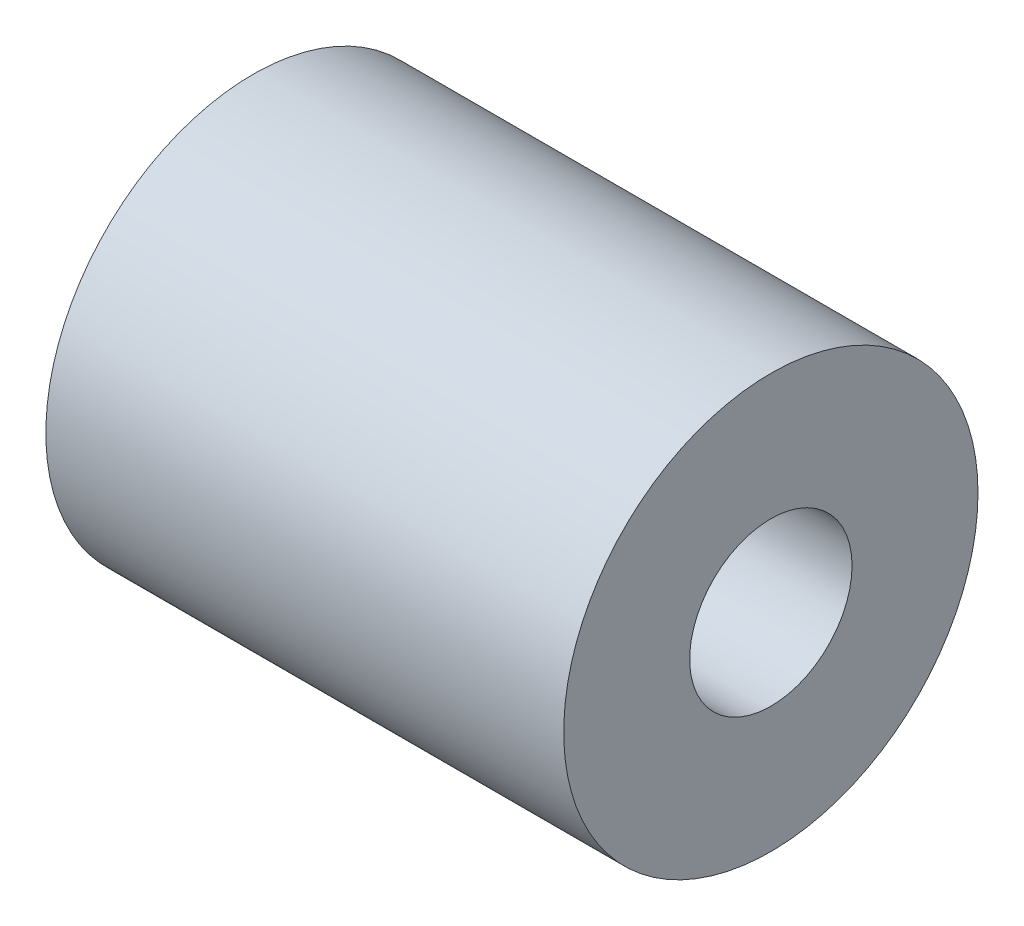
SolidWorks part; units mm, degrees
ref_plane "Front Plane" through (0, 0, 0) normal (0, 0, 1) x (1, 0, 0)
ref_plane "Top Plane" through (0, 0, 0) normal (0, 1, 0) x (1, 0, 0)
ref_plane "Right Plane" through (0, 0, 0) normal (1, 0, 0) x (0, 0, -1)
sketch "Sketch1" plane through (0, 0, 0) normal (1, 0, 0) x (0, 0, -1)
  circle A0 centre (0, 0) radius 6.35
  circle A1 centre (0, 0) radius 2.4892
extrude "Boss-Extrude1" add sketch "Sketch1" along normal blind 15.875
